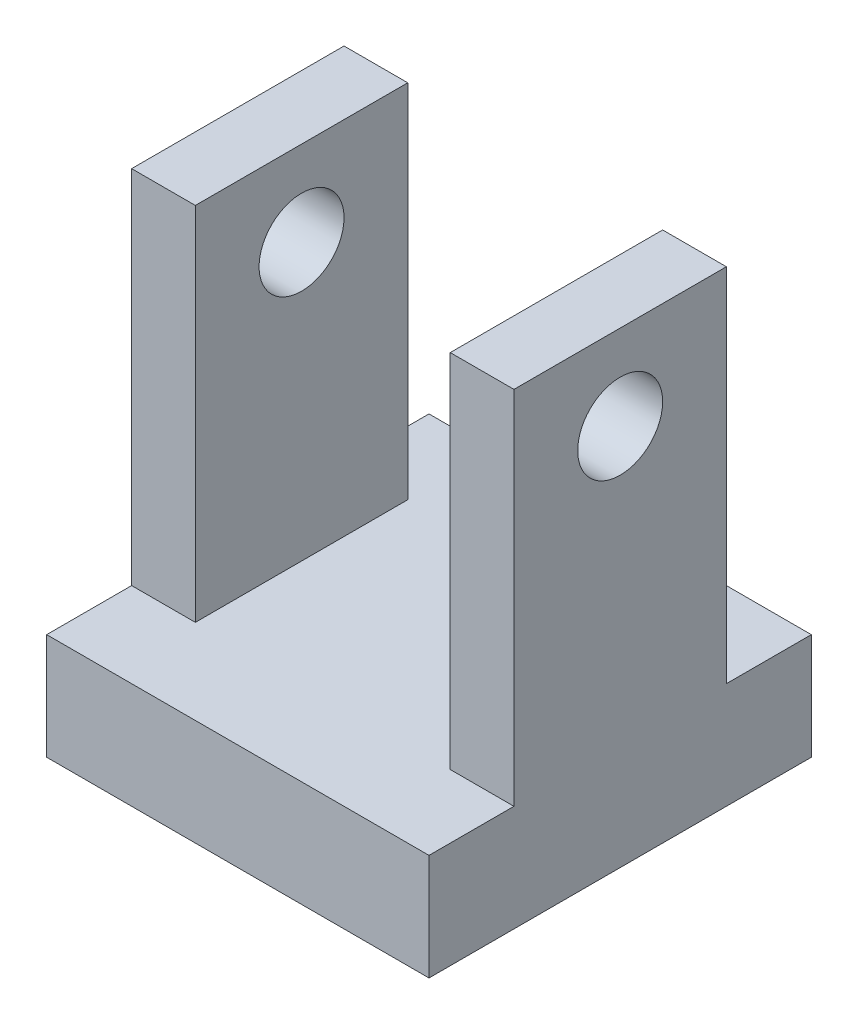
SolidWorks part; units mm, degrees
material "AISI 304"
ref_plane "Front Plane" through (0, 0, 0) normal (0, 0, 1) x (1, 0, 0)
ref_plane "Top Plane" through (0, 0, 0) normal (0, 1, 0) x (1, 0, 0)
ref_plane "Right Plane" through (0, 0, 0) normal (1, 0, 0) x (0, 0, -1)
sketch "Croquis1" plane through (0, 0, 0) normal (1, 0, 0) x (0, 0, -1)
  line L0 (45, 0) -> (-45, 0)
  line L1 (-45, 0) -> (-45, 25)
  line L2 (-45, 25) -> (-25, 25)
  line L3 (-25, 25) -> (-25, 110)
  line L4 (-25, 110) -> (25, 110)
  line L5 (25, 110) -> (25, 25)
  line L6 (25, 25) -> (45, 25)
  line L7 (45, 25) -> (45, 0)
  point P4 (0, 0)
  dimension "D1" = 90
  dimension "D2" = 25
  dimension "D3" = 50
  dimension "D4" = 20
  dimension "D5" = 110
extrude "Saliente-Extruir2" add sketch "Croquis1" along normal mid plane 90
sketch "Croquis4" plane through (0, 0, 25) normal (0, 0, 1) x (1, 0, 0)
  line L0 (0, 110) -> (-30, 110)
  line L1 (45, 110) -> (-45, 110) construction
  line L2 (-30, 110) -> (-30, 25)
  line L3 (45, 25) -> (-45, 25) construction
  line L4 (-30, 25) -> (30, 25)
  line L5 (30, 25) -> (30, 110)
  line L6 (30, 110) -> (0, 110)
  dimension "D1" = 60
  dimension "D2" = 30
extrude "Cortar-Extruir3" cut sketch "Croquis4" against normal blind 90
sketch "Croquis5" plane through (45, 0, 0) normal (1, 0, 0) x (0, 0, -1)
  line L0 (0, 0) -> (0, 90) construction
  circle A0 centre (0, 90) radius 10
  dimension "D2" = 20
  dimension "D1" = 90
extrude "Cortar-Extruir4" cut sketch "Croquis5" against normal blind 90
